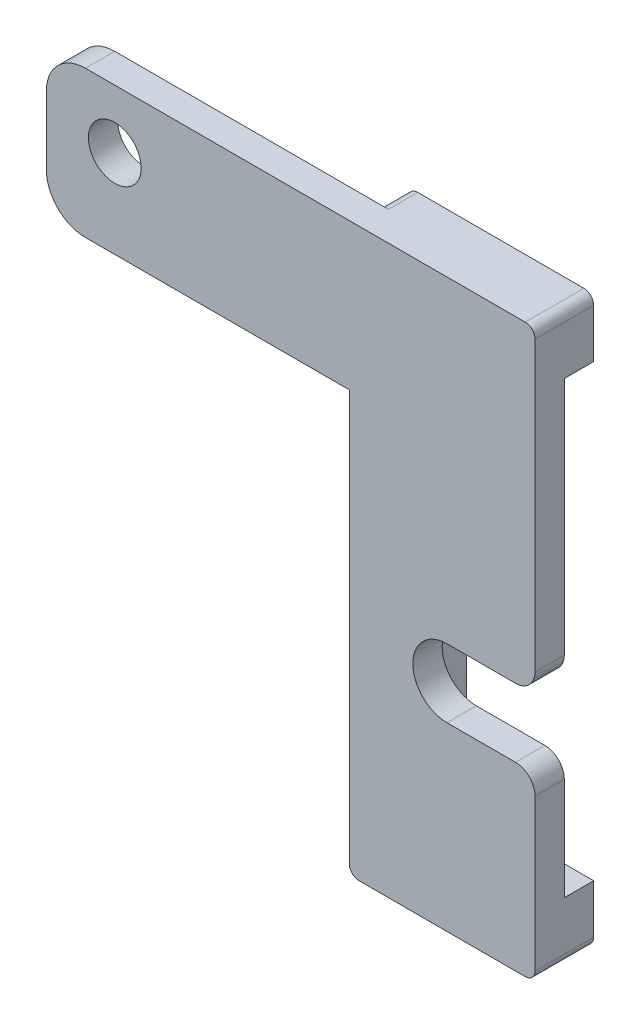
SolidWorks part; units mm, degrees
ref_plane "Front Plane" through (0, 0, 0) normal (0, 0, 1) x (1, 0, 0)
ref_plane "Top Plane" through (0, 0, 0) normal (0, 1, 0) x (1, 0, 0)
ref_plane "Right Plane" through (0, 0, 0) normal (1, 0, 0) x (0, 0, -1)
sketch "Sketch1" plane through (0, 0, 0) normal (0, 0, 1) x (1, 0, 0)
  line L0 (0, 0) -> (0, 15)
  line L1 (0, 15) -> (50, 15)
  line L2 (50, 15) -> (50, -43)
  line L3 (50, -43) -> (31, -43)
  line L4 (31, -43) -> (31, 0)
  line L5 (31, 0) -> (0, 0)
  circle A0 centre (7, 9) radius 2.7
  dimension "D7" = 5.4
  dimension "D1" = 15
  dimension "D2" = 31
  dimension "D3" = 43
  dimension "D4" = 19
  dimension "D5" = 24
  dimension "D6" = 6
extrude "Boss-Extrude1" add sketch "Sketch1" against normal blind 3
sketch "Sketch2" plane through (0, 0, -3) normal (0, 0, -1) x (-1, 0, 0)
  line L0 (-50, 15) -> (-50, 9)
  line L1 (-31, -43) -> (-50, -43)
  line L2 (-31, -43) -> (-31, 15)
  line L3 (-31, 15) -> (-50, 15)
  line L5 (-50, -43) -> (-50, 15) construction
  line L6 (-50, 9) -> (-37, 9)
  line L7 (-37, 9) -> (-37, -37)
  line L8 (-37, -37) -> (-50, -37)
  line L9 (-50, -37) -> (-50, -43)
  dimension "D1" = 6
  dimension "D2" = 6
  dimension "D3" = 6
extrude "Boss-Extrude2" add sketch "Sketch2" along normal blind 3
sketch "Sketch3" plane through (0, 0, 0) normal (0, 0, 1) x (1, 0, 0)
  line L0 (41, -17.5) -> (50, -17.5)
  line L1 (50, -43) -> (50, 15) construction
  line L2 (50, -17.5) -> (50, -24.5)
  line L3 (50, -24.5) -> (41, -24.5)
  line L4 (31, -43) -> (50, -43) construction
  arc A0 (41, -17.5) -> (41, -24.5) centre (41, -21) ccw
  dimension "D1" = 7
  dimension "D2" = 22
  dimension "D3" = 9
extrude "Cut-Extrude1" cut sketch "Sketch3" against normal blind 3
fillet "Fillet1" radius 4 2 edges at (0, 0, -1.5) (0, 15, -1.5)
fillet "Fillet2" radius 2 2 edges at (50, -17.5, -1.5) (50, -24.5, -1.5)
fillet "Fillet3" radius 1 4 edges at (50, 15, -3) (50, -43, -3) (31, -43, -3) (31, 15, -4.5)
